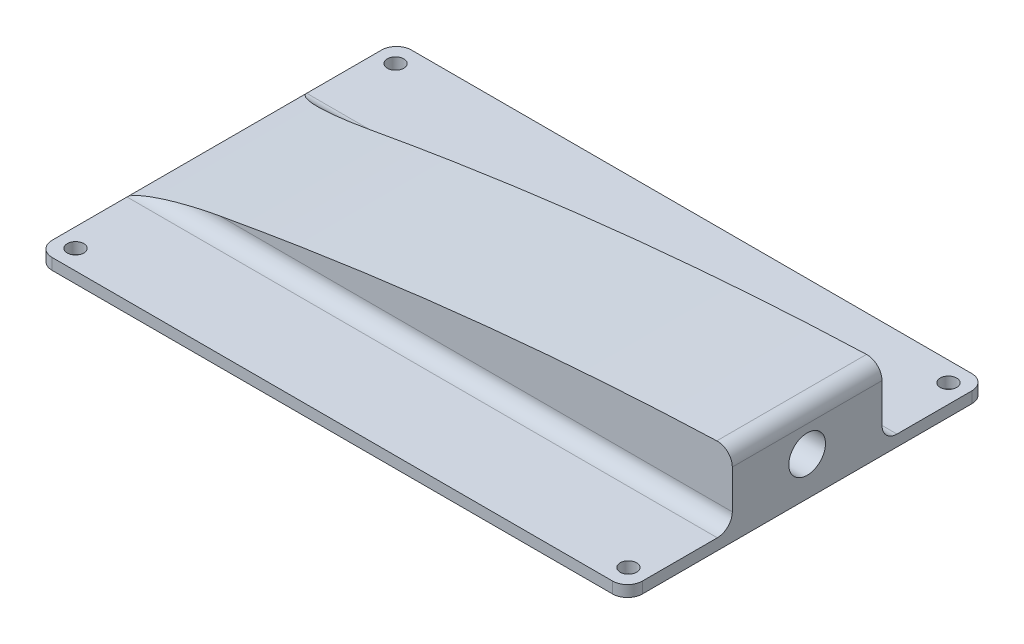
SolidWorks part; units mm, degrees
ref_plane "Front Plane" through (0, 0, 0) normal (0, 0, 1) x (1, 0, 0)
ref_plane "Top Plane" through (0, 0, 0) normal (0, 1, 0) x (1, 0, 0)
ref_plane "Right Plane" through (0, 0, 0) normal (1, 0, 0) x (0, 0, -1)
sketch "Sketch1" plane through (0, 0, 0) normal (0, 1, 0) x (1, 0, 0)
  line L1 (39.43, -24) -> (-39.43, -24)
  line L2 (39.43, -24) -> (39.43, 24)
  line L3 (39.43, 24) -> (-39.43, 24)
  line L4 (-39.43, -24) -> (-39.43, 24)
  line L5 (39.43, -24) -> (-39.43, 24) construction
  line L6 (39.43, 24) -> (-39.43, -24) construction
  point P0 (0, 0)
  point P6 (0, 0)
  dimension "D5" = 78.86
  dimension "D6" = 48
extrude "Boss-Extrude1" add sketch "Sketch1" along normal blind 1.5
sketch "Sketch2" plane through (0, 1.5, 0) normal (0, 1, 0) x (1, 0, 0)
  line L1 (36.93, -21.375) -> (-36.93, -21.375) construction
  line L2 (36.93, -21.375) -> (36.93, 21.375) construction
  line L3 (36.93, 21.375) -> (-36.93, 21.375) construction
  line L4 (-36.93, -21.375) -> (-36.93, 21.375) construction
  line L5 (36.93, -21.375) -> (-36.93, 21.375) construction
  line L6 (36.93, 21.375) -> (-36.93, -21.375) construction
  circle A0 centre (-36.93, 21.375) radius 1.1
  circle A1 centre (-36.93, -21.375) radius 1.1
  circle A2 centre (36.93, 21.375) radius 1.1
  circle A3 centre (36.93, -21.375) radius 1.1
  point P0 (0, 0)
  dimension "D3" = 2.2
  dimension "D1" = 73.86
  dimension "D2" = 42.75
extrude "Cut-Extrude1" cut sketch "Sketch2" against normal up to next
fillet "Fillet1" radius 2 4 edges at (-39.43, 0.75, -24) (39.43, 0.75, -24) (39.43, 0.75, 24) (-39.43, 0.75, 24)
sketch "Sketch3" plane through (0, 0, 0) normal (0, 0, 1) x (1, 0, 0)
  line L0 (39.43, 0.75) -> (39.43, 10.75)
  line L1 (39.43, 1.5) -> (39.43, 0) construction
  line L3 (39.43, 0.75) -> (-39.43, 0.75)
  line L5 (-39.43, 0) -> (-39.43, 1.5) construction
  line L6 (-39.43, 0.75) -> (-39.43, 1.5)
  spline S0 degree 2 poles (-39.43, 1.5) (-0.2512, 9.5172) (39.43, 10.75) knots 0 0 0 1 1 1
extrude "Boss-Extrude2" add sketch "Sketch3" along normal blind 10 and the other way blind 10
fillet "Fillet3" radius 2 2 edges at (0, 1.5, -10) (0, 1.5, 10)
fillet "Fillet5" radius 2 1 edges at (39.43, 10.75, 0)
sketch "Sketch4" plane through (39.43, 0, 0) normal (1, 0, 0) x (0, 0, -1)
  line L0 (0, 5.8753) -> (0, -5.8753) construction
  line L1 (10, 10.6823) -> (-10, 10.6823) construction
  circle A0 centre (0, 5.1823) radius 2.45
  dimension "D1" = 4.9
  dimension "D2" = 5.5
extrude "Cut-Extrude2" cut sketch "Sketch4" against normal blind 20
